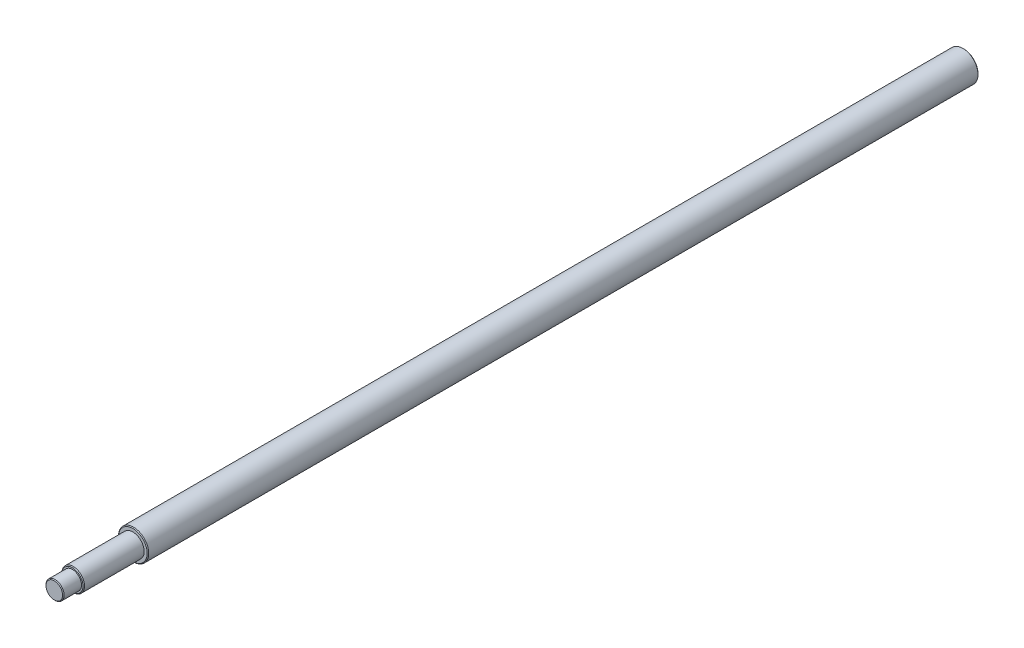
SolidWorks part; units mm, degrees
material "Chrome Stainless Steel"
ref_plane "Front Plane" through (0, 0, 0) normal (0, 0, 1) x (1, 0, 0)
ref_plane "Top Plane" through (0, 0, 0) normal (0, 1, 0) x (1, 0, 0)
ref_plane "Right Plane" through (0, 0, 0) normal (1, 0, 0) x (0, 0, -1)
sketch "Sketch1" plane through (0, 0, 0) normal (0, 0, 1) x (1, 0, 0)
  circle A0 centre (0, 0) radius 10
  dimension "D1" = 20
extrude "Boss-Extrude1" add sketch "Sketch1" along normal blind 550
cosmetic thread "Cosmetic Thread2" parameters "D2"=17
sketch "Sketch4" plane through (0, 0, 550) normal (0, 0, 1) x (1, 0, 0)
  circle A0 centre (0, 0) radius 7.5
  dimension "D1" = 15
extrude "Boss-Extrude2" add sketch "Sketch4" along normal blind 40
cosmetic thread "Cosmetic Thread1" parameters "D1"=15, "D2"=13
sketch "Sketch5" plane through (0, 0, 590) normal (0, 0, 1) x (1, 0, 0)
  circle A0 centre (0, 0) radius 6
  dimension "D1" = 12
extrude "Boss-Extrude3" add sketch "Sketch5" along normal blind 12
chamfer "Chamfer1" distance 0.5 angle 45 4 edges at (6, 0, 602) (10, 0, 0) (10, 0, 550) (7.5, 0, 590)
